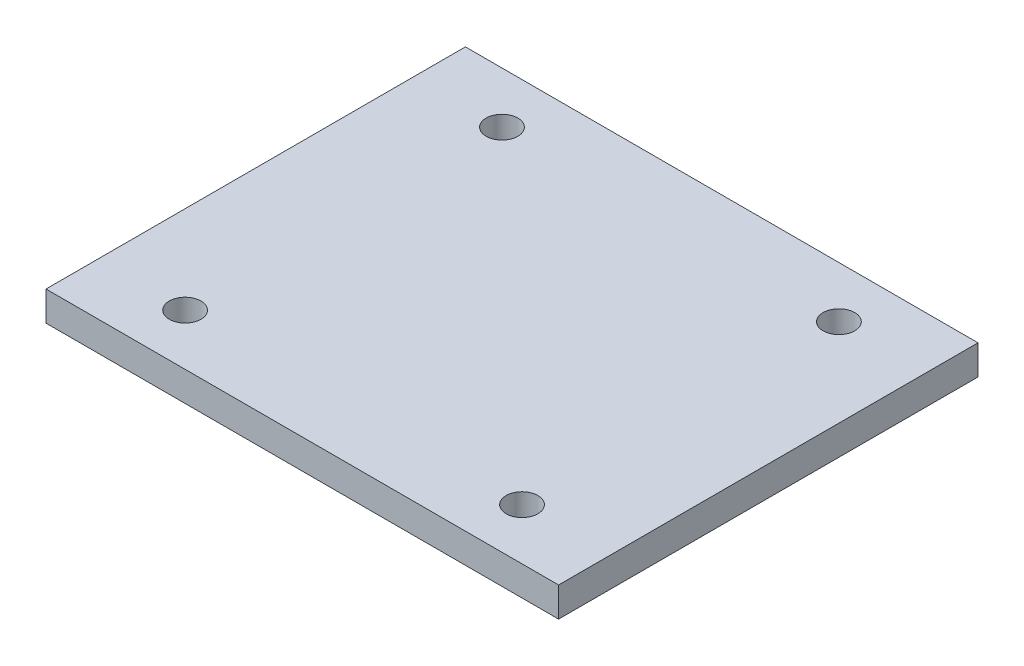
SolidWorks part; units mm, degrees
ref_plane "Front Plane" through (0, 0, 0) normal (0, 0, 1) x (1, 0, 0)
ref_plane "Top Plane" through (0, 0, 0) normal (0, 1, 0) x (1, 0, 0)
ref_plane "Right Plane" through (0, 0, 0) normal (1, 0, 0) x (0, 0, -1)
sketch "Sketch2" plane through (0, 0, 0) normal (0, 1, 0) x (1, 0, 0)
  line L0 (0, 0) -> (0, 90)
  line L1 (0, 90) -> (110, 90)
  line L2 (110, 90) -> (110, 0)
  line L3 (110, 0) -> (0, 0)
  dimension "D1" = 110
  dimension "D2" = 90
extrude "Boss-Extrude1" add sketch "Sketch2" along normal blind 6.35
sketch "Sketch3" plane through (0, 6.35, 0) normal (0, 1, 0) x (1, 0, 0)
  line L1 (110, 90) -> (0, 90) construction
  line L2 (0, 0) -> (110, 0) construction
  line L4 (55, 90) -> (55, 0) construction
  line L5 (0, 45) -> (55, 45) construction
  line L6 (55, 45) -> (110, 45) construction
  line L7 (0, 90) -> (0, 0) construction
  circle A0 centre (18.85, 79) radius 3.4
  circle A1 centre (18.85, 11) radius 3.4
  circle A2 centre (91.15, 11) radius 3.4
  circle A3 centre (91.15, 79) radius 3.4
  point P0 (0, 45)
  dimension "D4" = 6.8
  dimension "D3" = 11
  dimension "D2" = 18.85
extrude "Mounting Holes" cut sketch "Sketch3" against normal through all
equation "\"L1L\"=500"
equation "\"L1Thick\"=6.35"
equation "\"Harm-Drive-Outer\"=74.5"
equation "\"L1-Spacing\"=100"
equation "\"L-Bracket-HoleToWall\"=12.5"
equation "\"D3@Sketch3\"=\"L-Bracket-HoleToSide\""
equation "\"L-Bracket-HoleToSide\"=11"
equation "\"Bracket-Hole-D\"=6.8"
equation "\"D4@Sketch3\"=\"Bracket-Hole-D\""
equation "\"L1-Spacing\"=115.65"
equation "\"D2@Sketch3\"=\"L-Bracket-HoleToWall\"+\"L1Thick\""
